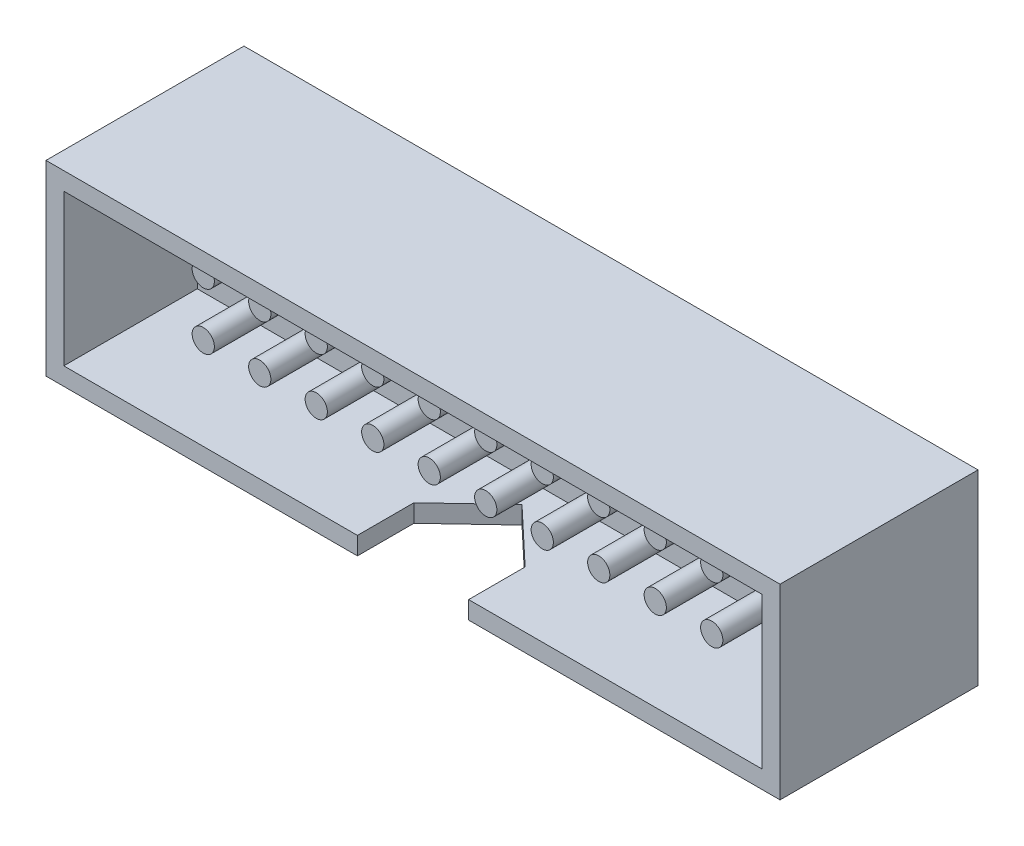
SolidWorks part; units mm, degrees
ref_plane "前视基准面" through (0, 0, 0) normal (0, 0, 1) x (1, 0, 0)
ref_plane "上视基准面" through (0, 0, 0) normal (0, 1, 0) x (1, 0, 0)
ref_plane "右视基准面" through (0, 0, 0) normal (1, 0, 0) x (0, 0, -1)
sketch "草图1" plane through (0, 0, 0) normal (0, 0, 1) x (1, 0, 0)
  line L1 (0, 0) -> (33, 0)
  line L2 (0, 0) -> (0, -8.4)
  line L3 (0, -8.4) -> (33, -8.4)
  line L4 (33, 0) -> (33, -8.4)
  dimension "D1" = 33
  dimension "D2" = 8.4
extrude "凸台-拉伸1" add sketch "草图1" along normal blind 8.9
sketch "草图2" plane through (0, 0, 8.9) normal (0, 0, 1) x (1, 0, 0)
  line L0 (0.8, -0.8) -> (32.2, -0.8)
  line L1 (33, 0) -> (0, 0) construction
  line L2 (0.8, -0.8) -> (0.8, -7.6)
  line L3 (0, 0) -> (0, -8.4) construction
  line L4 (0.8, -7.6) -> (32.2, -7.6)
  line L5 (0, -8.4) -> (33, -8.4) construction
  line L6 (32.2, -0.8) -> (32.2, -7.6)
  line L7 (33, -8.4) -> (33, 0) construction
  point P14 (33, -4.2)
  dimension "D1" = 0.8
  dimension "D2" = 0.8
  dimension "D3" = 0.8
  dimension "D4" = 0.8
extrude "切除-拉伸1" cut sketch "草图2" against normal blind 6
sketch "草图3" plane through (0, -8.4, 0) normal (0, -1, 0) x (1, 0, 0)
  line L0 (16.5, 8.9) -> (16.5, 0) construction
  line L1 (0, 8.9) -> (33, 8.9) construction
  line L2 (0, 0) -> (33, 0) construction
  line L3 (14, 8.9) -> (14, 6.36)
  line L4 (19, 8.9) -> (19, 6.36)
  line L5 (14, 8.9) -> (19, 8.9)
  line L6 (14, 6.36) -> (16.5, 4)
  line L7 (16.5, 4) -> (19, 6.36)
  dimension "D1" = 5
  dimension "D2" = 2.54
extrude "切除-拉伸2" cut sketch "草图3" against normal up to next
sketch "草图4" plane through (0, 0, 2.9) normal (0, 0, 1) x (1, 0, 0)
  line L0 (0.8, -4.2) -> (32.2, -4.2) construction
  line L1 (0.8, -0.8) -> (0.8, -7.6) construction
  line L2 (32.2, -7.6) -> (32.2, -0.8) construction
  line L3 (16.5, -0.8) -> (16.5, -7.6) construction
  line L4 (32.2, -0.8) -> (0.8, -0.8) construction
  line L5 (0.8, -7.6) -> (32.2, -7.6) construction
  circle A0 centre (20.31, -5.47) radius 0.5
  circle A1 centre (17.77, -2.93) radius 0.5
  circle A2 centre (20.31, -2.93) radius 0.5
  circle A3 centre (22.85, -5.47) radius 0.5
  circle A4 centre (22.85, -2.93) radius 0.5
  circle A5 centre (25.39, -5.47) radius 0.5
  circle A6 centre (17.77, -5.47) radius 0.5
  circle A7 centre (25.39, -2.93) radius 0.5
  circle A8 centre (27.93, -5.47) radius 0.5
  circle A9 centre (27.93, -2.93) radius 0.5
  circle A10 centre (5.07, -2.93) radius 0.5
  circle A11 centre (5.07, -5.47) radius 0.5
  circle A12 centre (7.61, -5.47) radius 0.5
  circle A13 centre (7.61, -2.93) radius 0.5
  circle A14 centre (10.15, -2.93) radius 0.5
  circle A15 centre (10.15, -5.47) radius 0.5
  circle A16 centre (12.69, -5.47) radius 0.5
  circle A17 centre (12.69, -2.93) radius 0.5
  circle A18 centre (15.23, -2.93) radius 0.5
  circle A19 centre (15.23, -5.47) radius 0.5
  dimension "D1" = 2.54
  dimension "D2" = 2.54
  dimension "D3" = 5
extrude "凸台-拉伸2" add sketch "草图4" along normal mid plane 8
